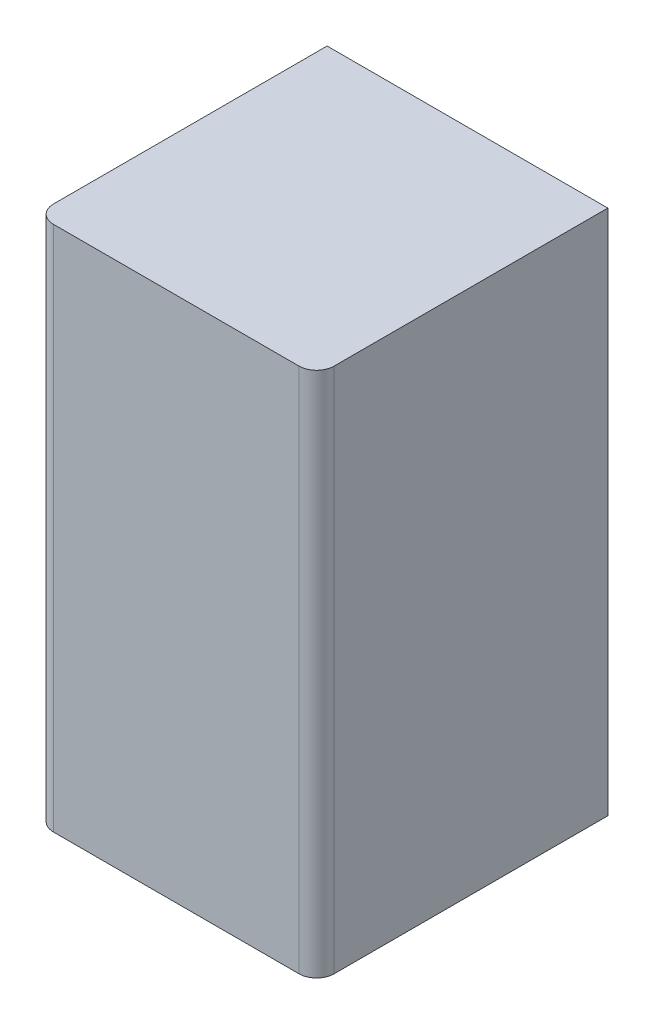
SolidWorks part; units mm, degrees
ref_plane "前视基准面" through (0, 0, 0) normal (0, 0, 1) x (1, 0, 0)
ref_plane "上视基准面" through (0, 0, 0) normal (0, 1, 0) x (1, 0, 0)
ref_plane "右视基准面" through (0, 0, 0) normal (1, 0, 0) x (0, 0, -1)
sketch "草图1" plane through (0, 0, 0) normal (0, 0, 1) x (1, 0, 0)
  line L0 (0, 48.626) -> (0, -83.7004) construction
  line L1 (-92.2698, 0) -> (95.8569, 0) construction
  line L2 (-8, 15) -> (8, 15)
  line L3 (-8, 15) -> (-8, -15)
  line L4 (-8, -15) -> (8, -15)
  line L5 (8, -15) -> (8, 15)
  dimension "D1" = 16
  dimension "D2" = 30
extrude "拉伸1" add sketch "草图1" along normal blind 0.1
sketch "草图2" plane through (0, 0, 0.1) normal (0, 0, 1) x (1, 0, 0)
  line L0 (0, 37.5456) -> (0, -35.199) construction
  line L1 (-34.3867, 0) -> (34.7477, 0) construction
  line L2 (-8, 15) -> (8, 15)
  line L3 (-8, 15) -> (-8, -15)
  line L4 (-8, -15) -> (8, -15)
  line L5 (8, -15) -> (8, 15)
  dimension "D1" = 16
  dimension "D2" = 30
extrude "拉伸2" add sketch "草图2" along normal blind 16.5
fillet "圆角1" radius 1 2 edges at (-8, 0, 16.6) (8, 0, 16.6)
